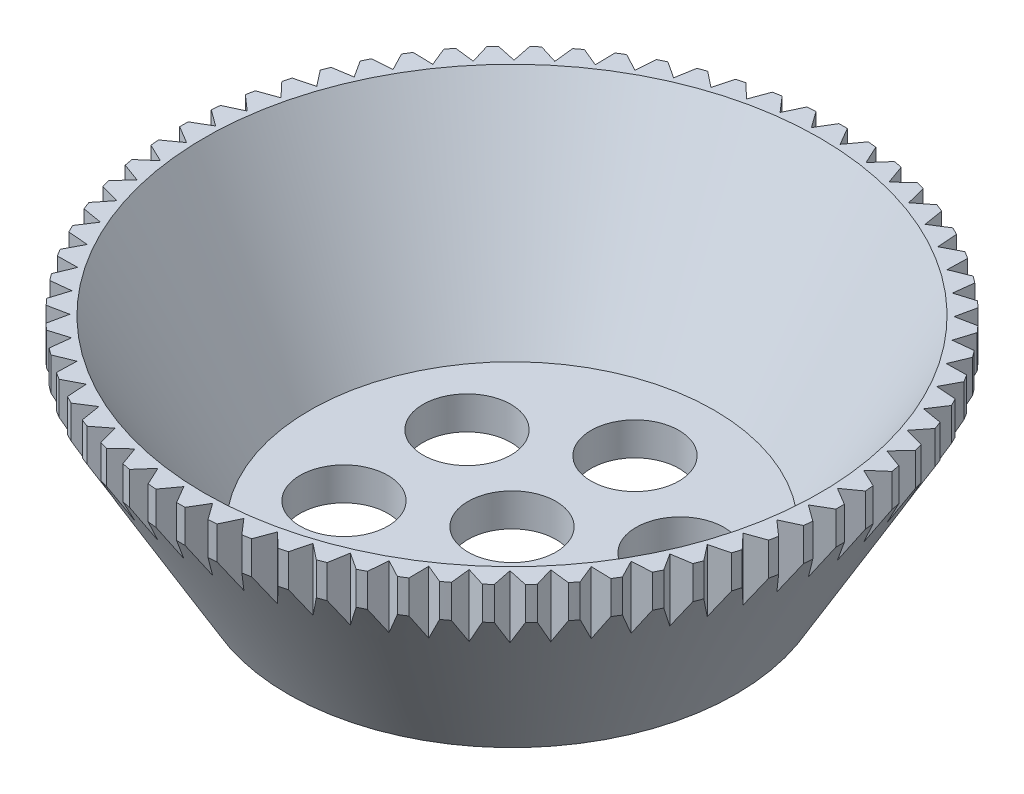
SolidWorks part; units mm, degrees
ref_plane "Front Plane" through (0, 0, 0) normal (0, 0, 1) x (1, 0, 0)
ref_plane "Top Plane" through (0, 0, 0) normal (0, 1, 0) x (1, 0, 0)
ref_plane "Right Plane" through (0, 0, 0) normal (1, 0, 0) x (0, 0, -1)
sketch "Sketch1" plane through (0, 0, 0) normal (0, 0, 1) x (1, 0, 0)
  line L1 (10.1935, 5.1749) -> (15, 13.5)
  line L2 (9.1935, 6.6749) -> (14, 15)
  line L4 (0, 5.1749) -> (10.1935, 5.1749) construction
  line L5 (0, 5.1749) -> (0, 15) construction
  line L6 (10.1935, 5.1749) -> (2, 5.1749)
  line L7 (2, 5.1749) -> (2, 6.6749)
  line L8 (2, 6.6749) -> (9.1935, 6.6749)
  line L9 (15, 13.5) -> (15, 15)
  line L10 (15, 15) -> (14, 15)
  dimension "D1" = 15
  dimension "D2" = 120
  dimension "D3" = 15
  dimension "D4" = 1
  dimension "D5" = 1.5
  dimension "D6" = 1.5
  dimension "D7" = 2
revolve "Revolve1" add sketch "Sketch1" angle 360 about L5
sketch "Sketch2" plane through (0, 15, 0) normal (0, 1, 0) x (1, 0, 0)
  line L0 (0.1232, -14.9995) -> (0.5914, -14.2148)
  line L1 (0.5914, -14.2148) -> (1.1232, -14.9579)
  arc A0 (0.1232, -14.9995) -> (1.1232, -14.9579) centre (0, 0) ccw
  circle A1 centre (0, 0) radius 15 construction
  dimension "D1" = 1
extrude "Cut-Extrude1" cut sketch "Sketch2" against normal blind 10
pattern_circular "CirPattern1" count 68 over 360 about axis through (0, 0, 0) along (0, 1, 0) of "Cut-Extrude1"
sketch "Sketch3" plane through (0, 6.6749, 0) normal (0, 1, 0) x (1, 0, 0)
  line L0 (0, 9.1935) -> (0, 2) construction
  circle A0 centre (0, 5.5967) radius 2
  circle A1 centre (0, 0) radius 9.1935 construction
  circle A2 centre (0, 0) radius 2 construction
  point P9 (0, 0)
  point P10 (0, 5.5967)
  dimension "D1" = 4
extrude "Cut-Extrude2" cut sketch "Sketch3" against normal through all
pattern_circular "CirPattern2" count 6 over 360 about axis through (0, 0, 0) along (0, 1, 0) of "Cut-Extrude2"
